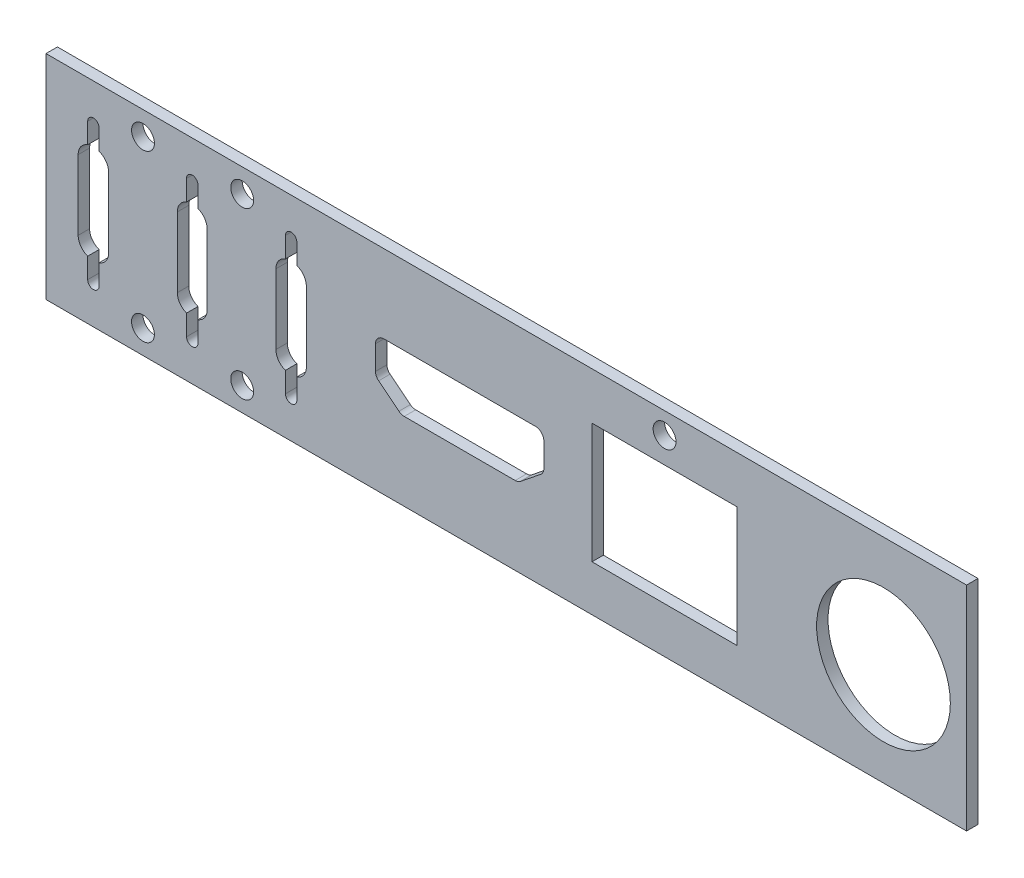
SolidWorks part; units mm, degrees
ref_plane "Front Plane" through (0, 0, 0) normal (0, 0, 1) x (1, 0, 0)
ref_plane "Top Plane" through (0, 0, 0) normal (0, 1, 0) x (1, 0, 0)
ref_plane "Right Plane" through (0, 0, 0) normal (1, 0, 0) x (0, 0, -1)
sketch "Sketch1" plane through (0, 0, 0) normal (0, 0, 1) x (1, 0, 0)
  line L1 (-32.0915, 17.4085) -> (48.445, 17.4085)
  line L2 (-32.0915, 17.4085) -> (-32.0915, -1.2309)
  line L3 (-32.0915, -1.2309) -> (48.445, -1.2309)
  line L4 (48.445, 17.4085) -> (48.445, -1.2309)
  line B0 (-27.8404, 12.3839) -> (-28.0516, 12.3839)
  line B1 (-29.278, 11.1575) -> (-29.278, 5.0425)
  line B2 (-26.614, 11.1575) -> (-26.614, 5.0425)
  line B3 (-27.8404, 3.8161) -> (-28.0516, 3.8161)
  line B4 (-19.2187, 3.8161) -> (-19.3733, 3.8161)
  line B5 (-20.5997, 11.1575) -> (-20.5997, 5.0425)
  line B6 (-17.9923, 11.1575) -> (-17.9923, 5.0425)
  line B7 (-19.2187, 12.3839) -> (-19.3733, 12.3839)
  line B8 (-10.5404, 12.3839) -> (-10.7516, 12.3839)
  line B9 (-11.978, 11.1575) -> (-11.978, 5.0425)
  line B10 (-10.5404, 3.8161) -> (-10.7516, 3.8161)
  line B11 (-9.314, 11.1575) -> (-9.314, 5.0425)
  line B12 (-2.9886, 7.167) -> (-1.2151, 5.7464)
  line B13 (-3.2645, 9.8371) -> (-3.2645, 7.7413)
  line B14 (10.728, 10.573) -> (-2.5286, 10.573)
  line B15 (11.4639, 9.8371) -> (11.4639, 7.7413)
  line B16 (11.188, 7.167) -> (9.4145, 5.7464)
  line B17 (8.9545, 5.5849) -> (-0.7551, 5.5849)
  line B18 (28.3749, 13.2913) -> (28.3749, 2.7854)
  line B19 (28.3749, 2.7854) -> (15.6749, 2.7854)
  line B20 (15.6749, 13.2913) -> (15.6749, 2.7854)
  line B21 (28.3749, 13.2913) -> (15.6749, 13.2913)
  line B22 (-14.9285, 15.35) -> (-14.9285, 0.85) construction
  line B23 (-11.978, 8.1) -> (-17.9923, 8.1) construction
  line B24 (-20.5997, 8.1) -> (-26.614, 8.1) construction
  line B25 (-23.6068, 15.35) -> (-23.6068, 0.85) construction
  circle B26 centre (41.1756, 7.7413) radius 5.85
  arc B27 (-28.0516, 12.3839) -> (-29.278, 11.1575) centre (-28.0516, 11.1575) ccw
  arc B28 (-26.614, 11.1575) -> (-27.8404, 12.3839) centre (-27.8404, 11.1575) ccw
  arc B29 (-27.8404, 3.8161) -> (-26.614, 5.0425) centre (-27.8404, 5.0425) ccw
  arc B30 (-29.278, 5.0425) -> (-28.0516, 3.8161) centre (-28.0516, 5.0425) ccw
  arc B31 (-19.2187, 3.8161) -> (-17.9923, 5.0425) centre (-19.2187, 5.0425) ccw
  arc B32 (-20.5997, 5.0425) -> (-19.3733, 3.8161) centre (-19.3733, 5.0425) ccw
  arc B33 (-19.3733, 12.3839) -> (-20.5997, 11.1575) centre (-19.3733, 11.1575) ccw
  arc B34 (-17.9923, 11.1575) -> (-19.2187, 12.3839) centre (-19.2187, 11.1575) ccw
  arc B35 (-10.7516, 12.3839) -> (-11.978, 11.1575) centre (-10.7516, 11.1575) ccw
  arc B36 (-9.314, 11.1575) -> (-10.5404, 12.3839) centre (-10.5404, 11.1575) ccw
  arc B37 (-11.978, 5.0425) -> (-10.7516, 3.8161) centre (-10.7516, 5.0425) ccw
  arc B38 (-10.5404, 3.8161) -> (-9.314, 5.0425) centre (-10.5404, 5.0425) ccw
  arc B39 (-1.2151, 5.7464) -> (-0.7551, 5.5849) centre (-0.7551, 6.3207) ccw
  arc B40 (-3.2645, 7.7413) -> (-2.9886, 7.167) centre (-2.5286, 7.7413) ccw
  arc B41 (-2.5286, 10.573) -> (-3.2645, 9.8371) centre (-2.5286, 9.8371) ccw
  arc B42 (11.4639, 9.8371) -> (10.728, 10.573) centre (10.728, 9.8371) ccw
  arc B43 (11.188, 7.167) -> (11.4639, 7.7413) centre (10.728, 7.7413) ccw
  arc B44 (8.9545, 5.5849) -> (9.4145, 5.7464) centre (8.9545, 6.3207) ccw
  circle B45 centre (-14.9285, 0.85) radius 1
  circle B46 centre (-23.6068, 0.85) radius 1
  circle B47 centre (-14.9285, 15.35) radius 1
  circle B48 centre (-23.6068, 15.35) radius 1
  circle B49 centre (22.0249, 15.5413) radius 1
  line B50 (-27.946, 12.3839) -> (-27.946, 3.8161) construction
  line B51 (-19.296, 12.3839) -> (-19.296, 3.8161) construction
  line B52 (-27.446, 14.1) -> (-27.446, 2.1)
  line B53 (-28.446, 14.1) -> (-28.446, 2.1)
  line B54 (-10.646, 12.3839) -> (-10.646, 3.8161) construction
  line B55 (-27.946, 14.1) -> (-27.946, 2.1) construction
  line B56 (-19.296, 14.1) -> (-19.296, 2.1) construction
  line B57 (-18.796, 14.1) -> (-18.796, 2.1)
  line B58 (-19.796, 14.1) -> (-19.796, 2.1)
  line B59 (-10.646, 14.1) -> (-10.646, 2.1) construction
  line B60 (-10.146, 14.1) -> (-10.146, 2.1)
  line B61 (-11.146, 14.1) -> (-11.146, 2.1)
  arc B62 (-27.446, 14.1) -> (-28.446, 14.1) centre (-27.946, 14.1) ccw
  arc B63 (-28.446, 2.1) -> (-27.446, 2.1) centre (-27.946, 2.1) ccw
  arc B64 (-18.796, 14.1) -> (-19.796, 14.1) centre (-19.296, 14.1) ccw
  arc B65 (-19.796, 2.1) -> (-18.796, 2.1) centre (-19.296, 2.1) ccw
  arc B66 (-10.146, 14.1) -> (-11.146, 14.1) centre (-10.646, 14.1) ccw
  arc B67 (-11.146, 2.1) -> (-10.146, 2.1) centre (-10.646, 2.1) ccw
sketch_block_instance "Side Connectors-1"
sketch_block "Side Connectors" parameters "D1"=2, "D3"=1.066, "D8"=11.2, "D2"=14.5, "D4"=10.5059, "D5"=12.7, "D6"=10.5059, "D7"=20.7082, "D9"=10.8327, "D10"=10.5059, "D11"=11.0493, "D12"=8.5679, "D13"=3
extrude "Boss-Extrude1" add sketch "Sketch1" along normal blind 1 contours L4 L1 L2 L3 B67 B61 B37 B9 B35 B66 B60 B36 B11 B38 B65 B58 B32 B5 B33 B64 B57 B34 B6 B31 B63 B53 B30 B1 B27 B62 B52 B28 B2 B29 B49 B48 B47 B46
